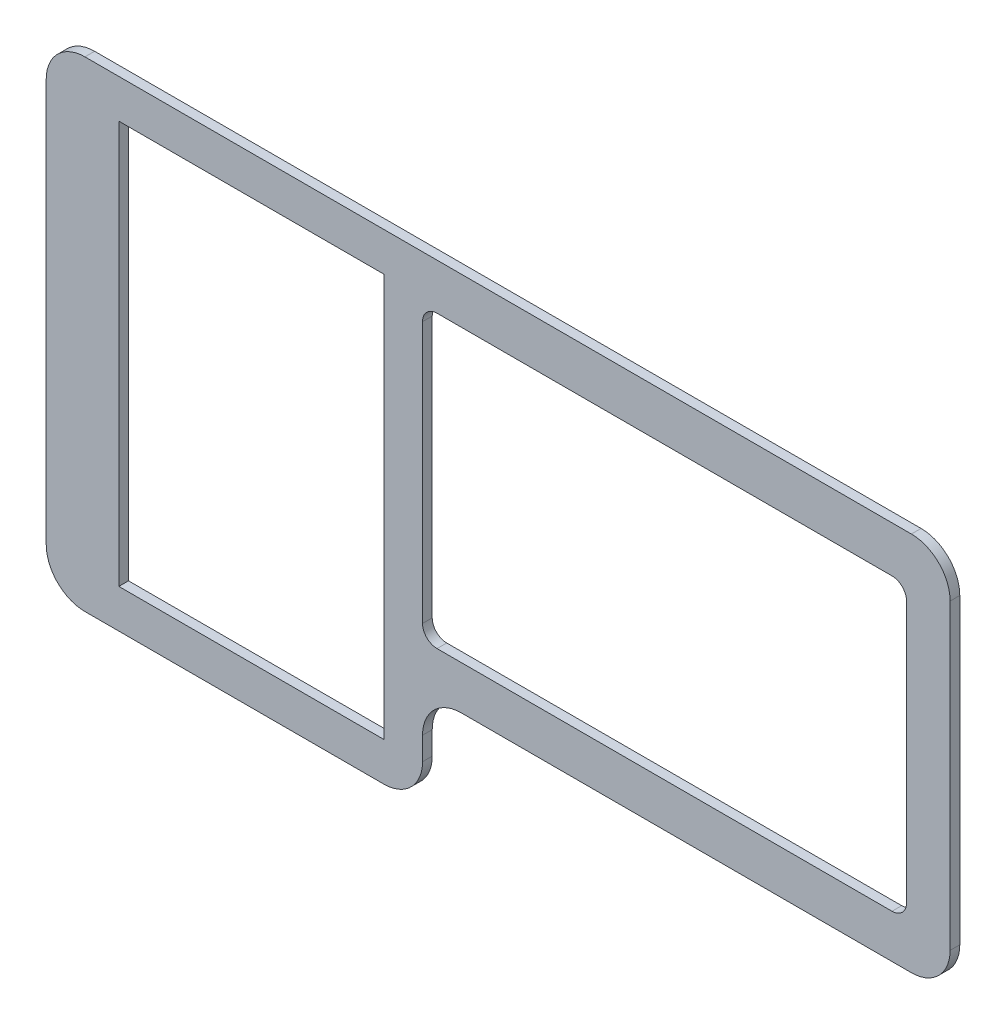
SolidWorks part; units mm, degrees
ref_plane "Front Plane" through (0, 0, 0) normal (0, 0, 1) x (1, 0, 0)
ref_plane "Top Plane" through (0, 0, 0) normal (0, 1, 0) x (1, 0, 0)
ref_plane "Right Plane" through (0, 0, 0) normal (1, 0, 0) x (0, 0, -1)
sketch "Sketch1" plane through (0, 0, 0) normal (0, 0, 1) x (1, 0, 0)
  line L0 (-50, -51.75) -> (-50, -47)
  line L1 (-47, 30) -> (47, 30)
  line L2 (-50, 27) -> (-50, -27)
  line L3 (-47, -30) -> (47, -30)
  line L4 (50, 27) -> (50, -27)
  line L5 (-112.75, 31.5) -> (-58, 31.5)
  line L6 (-112.75, 31.5) -> (-112.75, -51.75)
  line L7 (-112.75, -51.75) -> (-58, -51.75)
  line L8 (-58, 31.5) -> (-58, -51.75)
  line L9 (-119.75, 39.5) -> (51, 39.5)
  line L10 (-127.75, 31.5) -> (-127.75, -51.75)
  line L11 (-119.75, -59.75) -> (-58, -59.75)
  line L12 (59, 31.5) -> (59, -31)
  line L13 (-42, -39) -> (51, -39)
  arc A0 (51, -39) -> (59, -31) centre (51, -31) ccw
  arc A1 (51, 39.5) -> (59, 31.5) centre (51, 31.5) cw
  arc A2 (-119.75, 39.5) -> (-127.75, 31.5) centre (-119.75, 31.5) ccw
  arc A3 (-127.75, -51.75) -> (-119.75, -59.75) centre (-119.75, -51.75) ccw
  arc A4 (-50, -51.75) -> (-58, -59.75) centre (-58, -51.75) cw
  arc A5 (-50, -47) -> (-42, -39) centre (-42, -47) cw
  arc A6 (47, 30) -> (50, 27) centre (47, 27) cw
  arc A7 (47, -30) -> (50, -27) centre (47, -27) ccw
  arc A8 (-50, -27) -> (-47, -30) centre (-47, -27) ccw
  arc A9 (-47, 30) -> (-50, 27) centre (-47, 27) ccw
  point P4 (0, 30)
  point P6 (-50, 0)
  point P31 (50, 30)
  point P36 (-50, -30)
  point P39 (-50, 30)
  dimension "D12" = 8
  dimension "D13" = 3
  dimension "D1" = 100
  dimension "D2" = 60
  dimension "D3" = 54.75
  dimension "D4" = 83.25
  dimension "D5" = 9.5
  dimension "D6" = 8
  dimension "D7" = 9
  dimension "D8" = 15
  dimension "D9" = 8
  dimension "D10" = 8
  dimension "D11" = 9
extrude "Main extrude" add sketch "Sketch1" along normal blind 2
